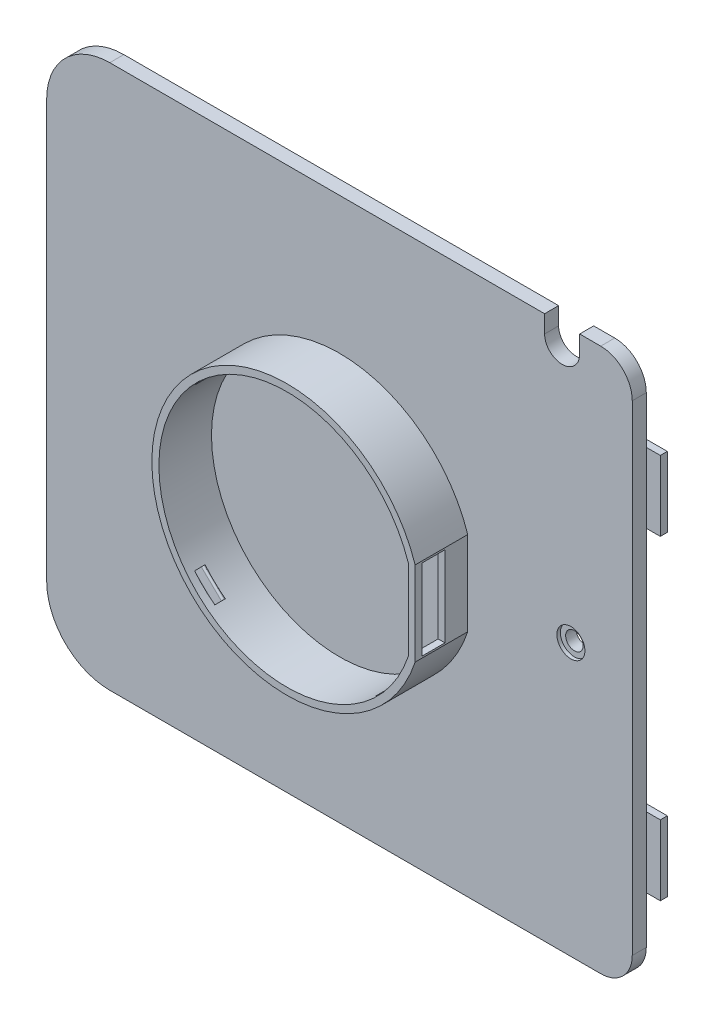
SolidWorks part; units mm, degrees
ref_plane "Front" through (0, 0, 0) normal (0, 0, 1) x (1, 0, 0)
ref_plane "Top" through (0, 0, 0) normal (0, 1, 0) x (1, 0, 0)
ref_plane "Right" through (0, 0, 0) normal (1, 0, 0) x (0, 0, -1)
sketch "ｽｹｯﾁ1" plane through (0, 0, 0) normal (0, 0, 1) x (1, 0, 0)
  line L1 (-83.5, 77.5) -> (83.5, 77.5)
  line L2 (-83.5, 77.5) -> (-83.5, -77.5)
  line L3 (-83.5, -77.5) -> (83.5, -77.5)
  line L4 (83.5, 77.5) -> (83.5, -77.5)
  line L5 (-83.5, 77.5) -> (83.5, -77.5) construction
  line L6 (-83.5, -77.5) -> (83.5, 77.5) construction
  point P0 (0, 0)
  dimension "D1" = 155
  dimension "D2" = 167
extrude "ﾎﾞｽ - 押し出し1" add sketch "ｽｹｯﾁ1" along normal blind 4
fillet "ﾌｨﾚｯﾄ1" radius 9 2 edges at (83.5, -77.5, 2) (83.5, 77.5, 2)
fillet "ﾌｨﾚｯﾄ2" radius 18 2 edges at (-83.5, -77.5, 2) (-83.5, 77.5, 2)
sketch "ｽｹｯﾁ2" plane through (0, 0, 4) normal (0, 0, 1) x (1, 0, 0)
  line L0 (74.5, 77.5) -> (-65.5, 77.5) construction
  line L1 (58.5, 77.5) -> (68.5, 77.5)
  line L2 (58.5, 77.5) -> (58.5, 72.5)
  line L4 (68.5, 77.5) -> (68.5, 72.5)
  line L5 (63.5, 77.5) -> (63.5, 62.7788) construction
  line L6 (83.5, -68.5) -> (83.5, 68.5) construction
  arc A0 (58.5, 72.5) -> (68.5, 72.5) centre (63.5, 72.5) ccw
  point P8 (0, 0)
  dimension "D4" = 5
  dimension "D1" = 20
  dimension "D2" = 10
  dimension "D3" = 5
extrude "ｶｯﾄ - 押し出し1" cut sketch "ｽｹｯﾁ2" against normal up to next
hole_wizard "穴1" positions "ｽｹｯﾁ9" profile "ｽｹｯﾁ10" legacy end condition up to next
sketch "ｽｹｯﾁ9" plane through (0, 0, 4) normal (0, 0, 1) x (1, 0, 0)
  line L0 (58.5, 77.5) -> (-65.5, 77.5) construction
  line L2 (83.5, -68.5) -> (83.5, 68.5) construction
  line L3 (-65.5, -77.5) -> (74.5, -77.5) construction
  point P0 (66, 0)
  dimension "D1" = 77.5
  dimension "D2" = 17.5
  dimension "D3" = 77.5
sketch "ｽｹｯﾁ10" plane through (66, 0, 4) normal (1, 0, 0) x (0, -1, 0)
  line L0 (0, 0) -> (0, 4)
  line L1 (0, 4) -> (2.5, 4)
  line L2 (2.5, 4) -> (2.5, 1)
  line L3 (2.5, 1) -> (4, 1)
  line L4 (4, 1) -> (4, 0)
  line L5 (4, 0) -> (0, 0)
  line L6 (0, 110) -> (0, -10) construction
  dimension "直径" = 5
  dimension "深さ" = 4
  dimension "座ぐり穴-直径" = 8
  dimension "座ぐり穴-深さ" = 1
sketch "ｽｹｯﾁ11" plane through (0, 0, 4) normal (0, 0, 1) x (1, 0, 0)
  line L0 (91.8904, 0) -> (-117.2241, 0) construction
  line L1 (34.641, 11.5) -> (34.641, -11.5)
  line L2 (36.5821, 12) -> (36.5821, -12)
  arc A2 (34.641, -11.5) -> (34.641, 11.5) centre (0, 0) cw
  arc A3 (36.5821, 12) -> (36.5821, -12) centre (0, 0) ccw
  dimension "D1" = 23
  dimension "D2" = 36.5
  dimension "D4" = 24
  dimension "D3" = 38.5
  dimension "D5" = 1.9411
extrude "ﾎﾞｽ - 押し出し3" add sketch "ｽｹｯﾁ11" along normal blind 15
sketch "ｽｹｯﾁ13" plane through (36.5821, 0, 0) normal (1, 0, 0) x (0, 0, -1)
  line L0 (11.4447, 0) -> (-37.1117, 0) construction
  line L1 (-17, 11.5) -> (-10.5, 11.5)
  line L2 (-17, 11.5) -> (-17, -11.5)
  line L3 (-17, -11.5) -> (-10.5, -11.5)
  line L4 (-10.5, 11.5) -> (-10.5, -11.5)
  line L5 (-4, -12) -> (-4, 12) construction
  dimension "D1" = 6.5
  dimension "D2" = 6.5
  dimension "D3" = 23
extrude "ｶｯﾄ - 押し出し2" cut sketch "ｽｹｯﾁ13" against normal up to next
sketch "ｽｹｯﾁ14" plane through (0, 0, 0) normal (0, 1, 0) x (1, 0, 0)
  line L0 (0, 0) -> (5.3431, -124.3448) construction
ref_plane "平面1" through (0, 0, 0) normal (-0.7065, 0.7071, 0.0304) x (0.7076, 0.7065, 0.0126)
ref_plane "平面2" through (-24.7259, 24.7487, 1.0625) normal (-0.7065, 0.7071, 0.0304) x (0.7076, 0.7065, 0.0126)
sketch "ｽｹｯﾁ15" plane through (-24.7259, 24.7487, 1.0625) normal (-0.7065, 0.7071, 0.0304) x (0.7076, 0.7065, 0.0126)
  line L0 (0, -53.3214) -> (0, 75.9558) construction
  line L1 (12.9242, -17.7906) -> (-21.95, -17.7906) construction
  line L2 (-4, -15.7906) -> (4, -15.7906)
  line L3 (-4, -15.7906) -> (-4, -12.7906)
  line L4 (-4, -12.7906) -> (4, -12.7906)
  line L5 (4, -15.7906) -> (4, -12.7906)
  ellipse E1 centre (0.2387, -18.9897) end of major axis (-36.2584, -19.4485) minor radius 1.108 (32.8765, -19.0758) -> (16.6281, -19.774) ccw construction
  dimension "D1" = 3
  dimension "D2" = 2
  dimension "D3" = 8
extrude "ｶｯﾄ - 押し出し3" cut sketch "ｽｹｯﾁ15" along normal blind 2.5
fillet "ﾌｨﾚｯﾄ3" radius 0.5 2 edges at (-26.3314, 26.1282, 13.9221) (-26.2937, 26.0372, 16.9204)
pattern_circular "円形ﾊﾟﾀｰﾝ1" count 4 every 90 about axis through (0, 0, 0) along (0, 0, 1) of "ｶｯﾄ - 押し出し3", "ﾌｨﾚｯﾄ3"
ref_plane "平面3" through (36.5821, 12, 19) normal (0, 1, 0) x (1, 0, 0)
sketch "ｽｹｯﾁ18" plane through (0, 0, 0) normal (0, 0, -1) x (-1, 0, 0)
  line L0 (-66, 0) -> (-100.9232, 0) construction
  line L1 (-83.5, -68.5) -> (-83.5, 68.5) construction
  line L2 (-77.5, 35) -> (-87.5, 35)
  line L3 (-77.5, 35) -> (-77.5, 55)
  line L4 (-77.5, 55) -> (-87.5, 55)
  line L5 (-87.5, 35) -> (-87.5, 55)
  line L6 (-83.5, -68.5) -> (-83.5, 68.5) construction
  dimension "D1" = 55
  dimension "D2" = 20
  dimension "D3" = 10
  dimension "D4" = 4
extrude "ﾎﾞｽ - 押し出し4" add sketch "ｽｹｯﾁ18" along normal blind 2
fillet "ﾌｨﾚｯﾄ4" radius 1 1 edges at (77.5, 45, -2)
mirror "ﾐﾗｰ1" about plane through (0, 0, 0) normal (0, 1, 0) of "ﾎﾞｽ - 押し出し4", "ﾌｨﾚｯﾄ4"
